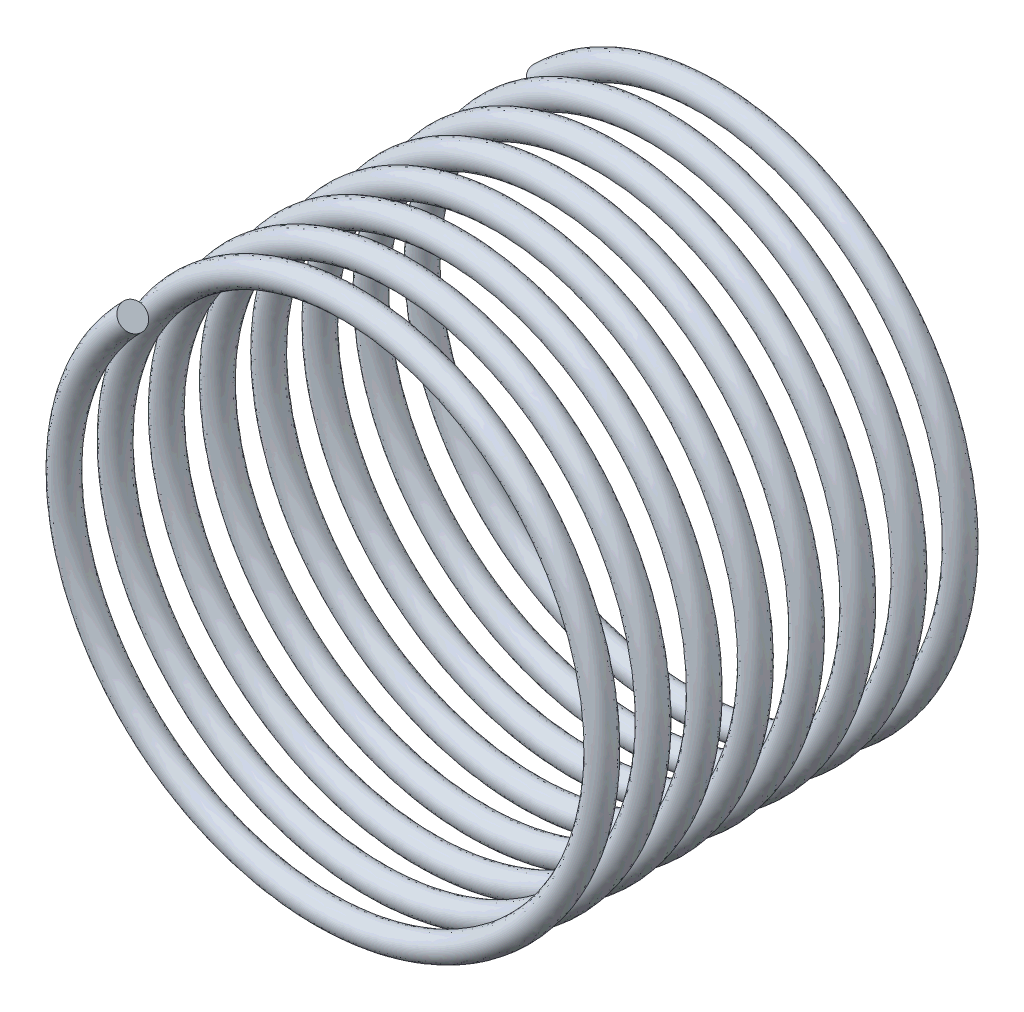
SolidWorks part; units mm, degrees
ref_plane "Front Plane" through (0, 0, 0) normal (0, 0, 1) x (1, 0, 0)
ref_plane "Top Plane" through (0, 0, 0) normal (0, 1, 0) x (1, 0, 0)
ref_plane "Right Plane" through (0, 0, 0) normal (1, 0, 0) x (0, 0, -1)
sketch "Sketch1" plane through (0, 0, 0) normal (0, 0, 1) x (1, 0, 0)
  circle A0 centre (0, 0) radius 50
  dimension "D1" = 100
curve "Helix/Spiral2" pitch 10 height 80 turns 8
sweep "Sweep1" add path "Helix/Spiral2" circular profile diameter 5 parameters "D3"=5
